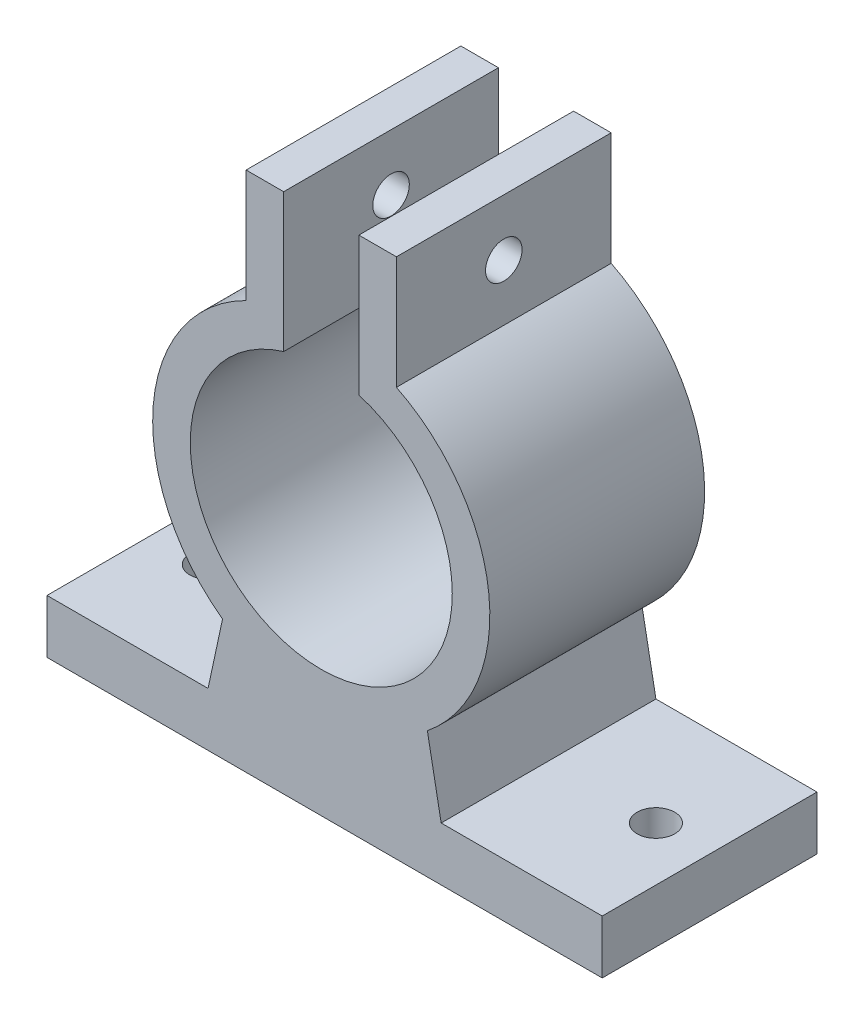
SolidWorks part; units mm, degrees
ref_plane "Ön Düzlem" through (0, 0, 0) normal (0, 0, 1) x (1, 0, 0)
ref_plane "Üst Düzlem" through (0, 0, 0) normal (0, 1, 0) x (1, 0, 0)
ref_plane "Sağ Düzlem" through (0, 0, 0) normal (1, 0, 0) x (0, 0, -1)
sketch "Çizim1" plane through (0, 0, 0) normal (0, 0, 1) x (1, 0, 0)
  line L0 (-3.5, 20.5805) -> (-3.5, 24.5805)
  line L1 (-3.5, 24.5805) -> (-7, 24.5805)
  line L2 (-9.0799, -12.2) -> (-15.7, -43)
  line L3 (9.8818, -12.2) -> (15.7, -43)
  line L4 (-15.7, -43) -> (15.7, -43)
  line L5 (-3.5, 11.6872) -> (-3.5, 20.5805)
  line L7 (-7, 20.5805) -> (-7, 14.0531)
  line L8 (3.5, 11.6872) -> (3.5, 20.5805)
  line L10 (7, 20.5805) -> (7, 14.0531)
  line L11 (-7, 24.5805) -> (-7, 20.5805)
  line L12 (3.5, 20.5805) -> (3.5, 24.5805)
  line L13 (3.5, 24.5805) -> (7, 24.5805)
  line L14 (7, 24.5805) -> (7, 20.5805)
  arc A0 (-3.5, 11.6872) -> (3.5, 11.6872) centre (0, 0) ccw
  arc A1 (-7, 14.0531) -> (-9.1932, -12.727) centre (0, 0) ccw
  arc A2 (9.8818, -12.2) -> (7, 14.0531) centre (0, 0) ccw
  dimension "D1" = 24.4
  dimension "D2" = 31.4
extrude "Yükseklik-Ekstrüzyon1" add sketch "Çizim1" along normal blind 20
sketch "Çizim6" plane through (7, 0, 0) normal (1, 0, 0) x (0, 0, -1)
  circle A0 centre (-10, 19.3168) radius 1.7
extrude "Kes-Ekstrüzyon2" cut sketch "Çizim6" against normal blind 20
sketch "Çizim7" plane through (0, 0, 20) normal (0, 0, 1) x (1, 0, 0)
  line L0 (-15.7, -43) -> (-15.7, -19)
  line L1 (-15.7, -19) -> (23.8218, -19)
  line L2 (23.8218, -19) -> (23.8218, -48.3755)
  line L3 (23.8218, -48.3755) -> (-15.7, -48.3755)
  line L4 (-15.7, -48.3755) -> (-15.7, -43)
extrude "Kes-Ekstrüzyon3" cut sketch "Çizim7" against normal blind 46
sketch "Çizim8" plane through (0, 0, 20) normal (0, 0, 1) x (1, 0, 0)
  line L0 (-10.5415, -19) -> (-25.5415, -19)
  line L1 (-25.5415, -19) -> (-25.5415, -24)
  line L2 (-25.5415, -24) -> (11.1663, -24)
  line L3 (11.1663, -24) -> (26.1663, -24)
  line L4 (26.1663, -24) -> (26.1663, -19)
  line L5 (26.1663, -19) -> (11.1663, -19)
  line L6 (11.1663, -19) -> (-10.5415, -19)
extrude "Yükseklik-Ekstrüzyon2" add sketch "Çizim8" against normal up to surface (20 mm away) up to face at (0.0773, 5.3661, 0)
sketch "Çizim9" plane through (0, -19, 0) normal (0, 1, 0) x (1, 0, 0)
  line L0 (-25.5415, 0) -> (-25.5415, -20) construction
  line L1 (26.1663, 0) -> (26.1663, -20) construction
  circle A0 centre (-20.5415, -10) radius 1.7
  circle A1 centre (21.1663, -10) radius 1.75
  dimension "D1" = 5
  dimension "D2" = 5
extrude "Kes-Ekstrüzyon4" cut sketch "Çizim9" against normal blind 46
